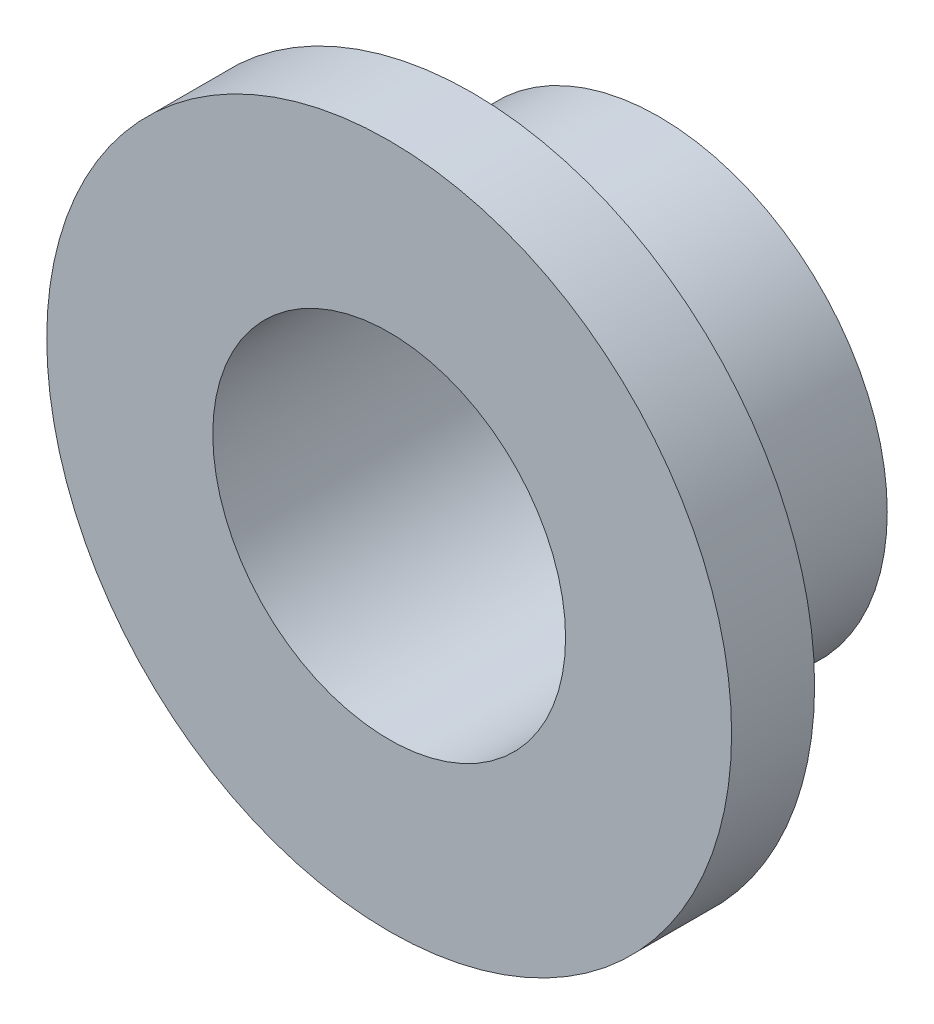
SolidWorks part; units mm, degrees
ref_plane "Alzado" through (0, 0, 0) normal (0, 0, 1) x (1, 0, 0)
ref_plane "Planta" through (0, 0, 0) normal (0, 1, 0) x (1, 0, 0)
ref_plane "Vista lateral" through (0, 0, 0) normal (1, 0, 0) x (0, 0, -1)
sketch "Croquis1" plane through (0, 0, 0) normal (0, 0, 1) x (1, 0, 0)
  circle A0 centre (0, 0) radius 8.25
  circle A1 centre (0, 0) radius 4.25
  dimension "D1" = 8.5
  dimension "D2" = 16.5
extrude "Saliente-Extruir1" add sketch "Croquis1" against normal blind 2
sketch "Croquis2" plane through (0, 0, -2) normal (0, 0, -1) x (-1, 0, 0)
  circle A0 centre (0, 0) radius 4.25
  circle A1 centre (0, 0) radius 5.5
  dimension "D1" = 11
extrude "Saliente-Extruir2" add sketch "Croquis2" along normal blind 4.5
